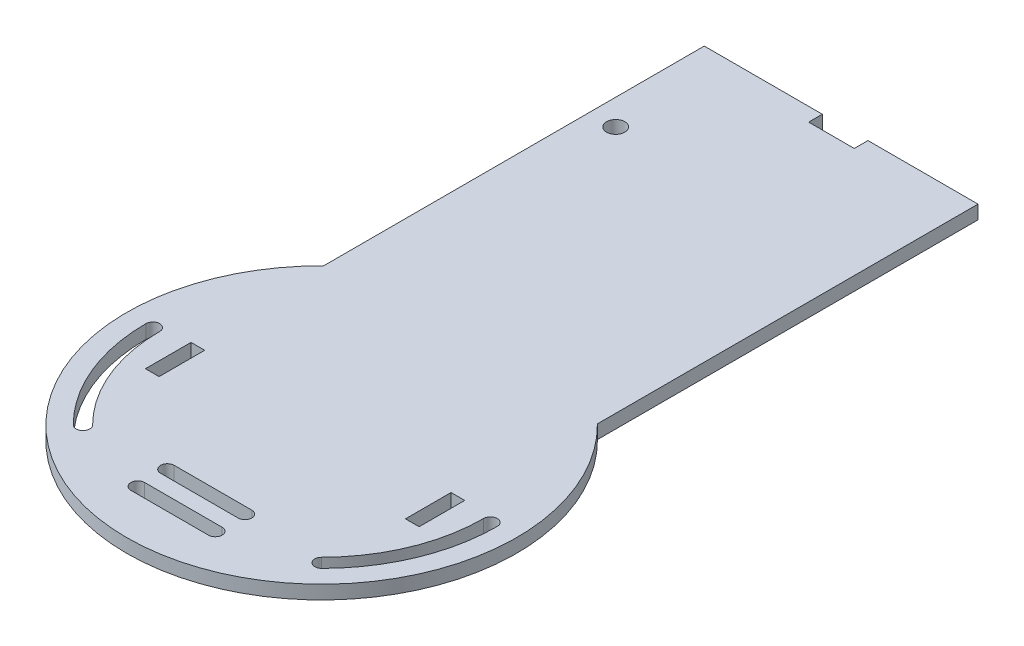
SolidWorks part; units mm, degrees
material "Acrílico (Impacto medio-alto)"
ref_plane "Alzado" through (0, 0, 0) normal (0, 0, 1) x (1, 0, 0)
ref_plane "Planta" through (0, 0, 0) normal (0, 1, 0) x (1, 0, 0)
ref_plane "Vista lateral" through (0, 0, 0) normal (1, 0, 0) x (0, 0, -1)
sketch "Croquis1" plane through (0, 0, 0) normal (0, 1, 0) x (1, 0, 0)
  line L0 (-4.0691, 62.5) -> (-4.0691, 59.5) construction
  line L2 (-29.9452, -20.9242) -> (-29.9452, 62.5)
  line L3 (-29.9452, 62.5) -> (-4.0691, 62.5)
  line L4 (30.0548, -20.9242) -> (30.0548, 62.5)
  line L5 (-30.0343, -62.4572) -> (30.0548, 62.5) construction
  line L6 (-29.9452, 62.5) -> (29.9451, -62.5) construction
  line L7 (5.9309, 59.5) -> (-4.0691, 59.5) construction
  line L8 (5.9309, 62.5) -> (5.9309, 59.5) construction
  line L9 (-4.0691, 62.5) -> (-4.0691, 59.5)
  line L10 (5.9309, 59.5) -> (-4.0691, 59.5)
  line L11 (5.9309, 62.5) -> (5.9309, 59.5)
  line L12 (5.9309, 62.5) -> (30.0548, 62.5)
  line L13 (30.0548, -50) -> (27.0548, -50) construction
  line L14 (27.0548, -60) -> (27.0548, -50) construction
  line L15 (30.0548, -60) -> (27.0548, -60) construction
  line L16 (30.0548, -60) -> (30.0548, -50) construction
  line L17 (-26.9452, -60) -> (-26.9452, -50) construction
  line L18 (-26.9452, -60) -> (-29.9452, -60) construction
  line L19 (-29.9452, -60) -> (-29.9452, -50) construction
  line L20 (-26.9452, -50) -> (-29.9452, -50) construction
  line L21 (30.0548, -50) -> (27.0548, -50)
  line L22 (27.0548, -60) -> (27.0548, -50)
  line L23 (30.0548, -60) -> (27.0548, -60)
  line L24 (30.0548, -60) -> (30.0548, -50)
  line L25 (-26.9452, -60) -> (-26.9452, -50)
  line L26 (-26.9452, -60) -> (-29.9452, -60)
  line L27 (-29.9452, -60) -> (-29.9452, -50)
  line L28 (-26.9452, -50) -> (-29.9452, -50)
  line L31 (8.5548, -75.1826) -> (-8.4452, -75.1826)
  line L32 (-8.4452, -78.1826) -> (8.5548, -78.1826)
  line L33 (8.5548, -81.6826) -> (-8.4452, -81.6826)
  line L34 (-8.4452, -84.6826) -> (8.5548, -84.6826)
  line L37 (0.0548, -51.3691) -> (0.0548, -94.1112) construction
  arc A0 (-29.9452, -20.9242) -> (30.0548, -20.9242) centre (0.0548, -51.3691) ccw
  arc A1 (-8.4452, -81.6826) -> (-8.4452, -84.6826) centre (-8.4452, -83.1826) ccw
  circle A3 centre (-24.3, 37.4392) radius 2
  arc A6 (8.5548, -84.6826) -> (8.5548, -81.6826) centre (8.5548, -83.1826) ccw
  arc A10 (-8.4452, -75.1826) -> (-8.4452, -78.1826) centre (-8.4452, -76.6826) ccw
  arc A11 (8.5548, -78.1826) -> (8.5548, -75.1826) centre (8.5548, -76.6826) ccw
  arc A13 (25.1571, -76.4714) -> (35.5548, -51.3691) centre (0.0548, -51.3691) ccw
  arc A14 (27.2785, -78.5927) -> (38.5548, -51.3691) centre (0.0548, -51.3691) ccw
  arc A15 (-35.4452, -51.3691) -> (-25.0474, -76.4714) centre (0.0548, -51.3691) ccw
  arc A17 (-38.4452, -51.3691) -> (-27.1688, -78.5927) centre (0.0548, -51.3691) ccw
  arc A21 (-27.1688, -78.5927) -> (-25.0474, -76.4714) centre (-26.1081, -77.532) ccw
  arc A22 (-35.4452, -51.3691) -> (-38.4452, -51.3691) centre (-36.9452, -51.3691) ccw
  arc A23 (25.1571, -76.4714) -> (27.2785, -78.5927) centre (26.2178, -77.532) ccw
  arc A24 (38.5548, -51.3691) -> (35.5548, -51.3691) centre (37.0548, -51.3691) ccw
  point P0 (0, 0)
  dimension "D3" = 4
  dimension "D4" = 3
  dimension "D5" = 3
  dimension "D7" = 1.5
  dimension "D1" = 125
  dimension "D2" = 60
  dimension "D6" = 3.5
  dimension "D8" = 17
  dimension "D9" = 17
  dimension "D10" = 8.5
extrude "Saliente-Extruir1" add sketch "Croquis1" along normal blind 3
